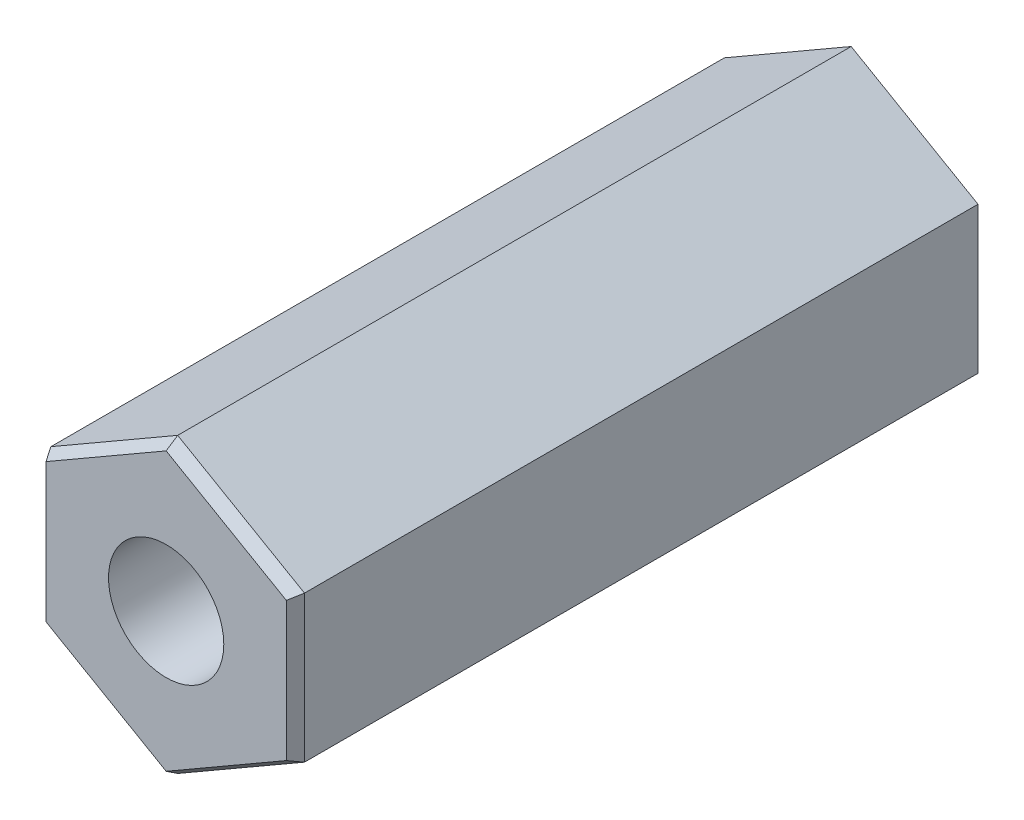
SolidWorks part; units mm, degrees
material "KS26"
ref_plane "正面" through (0, 0, 0) normal (0, 0, 1) x (1, 0, 0)
ref_plane "平面" through (0, 0, 0) normal (0, 1, 0) x (1, 0, 0)
ref_plane "右側面" through (0, 0, 0) normal (1, 0, 0) x (0, 0, -1)
sketch "ｽｹｯﾁ1" plane through (0, 0, 0) normal (0, 0, 1) x (1, 0, 0)
  line L1 (-2.75, 1.5877) -> (-2.75, -1.5877)
  line L2 (-2.75, -1.5877) -> (0, -3.1754)
  line L3 (0, -3.1754) -> (2.75, -1.5877)
  line L4 (2.75, -1.5877) -> (2.75, 1.5877)
  line L5 (2.75, 1.5877) -> (0, 3.1754)
  line L6 (0, 3.1754) -> (-2.75, 1.5877)
  circle A0 centre (0, 0) radius 2.75 construction
  dimension "D1" = 5.5
extrude "ﾎﾞｽ - 押し出し1" add sketch "ｽｹｯﾁ1" along normal mid plane 15
hole_wizard "M3 ねじ穴1" positions "ｽｹｯﾁ2" profile "ｽｹｯﾁ3" tap size "M3" standard "JIS" end condition through all
sketch "ｽｹｯﾁ2" plane through (0, 0, 7.5) normal (0, 0, 1) x (1, 0, 0)
  point P0 (0, 0)
cosmetic thread "穴のねじ山1" parameters "D2"=3
sketch "ｽｹｯﾁ3" plane through (0, 0, 7.5) normal (1, 0, 0) x (0, -1, 0)
  line L0 (0, 0) -> (0, 15)
  line L1 (0, 15) -> (1.25, 15)
  line L2 (1.25, 15) -> (1.25, 0)
  line L5 (1.25, 0) -> (0, 0)
  line L11 (0, -6.35) -> (0, 107.95) construction
  dimension "次ｻｰﾌｪｽまでのねじ下穴ﾄﾞﾘﾙ直径" = 2.5
  dimension "次ｻｰﾌｪｽまでのねじ下穴ﾄﾞﾘﾙの深さ" = 15
sketch "ｽｹｯﾁ4" plane through (0, 0, -7.5) normal (0, 0, -1) x (-1, 0, 0)
  circle A0 centre (0, 0) radius 1.5
  dimension "D1" = 3
extrude "ﾎﾞｽ - 押し出し2" [suppressed] add sketch "ｽｹｯﾁ4" along normal blind 6
chamfer "面取り1" [suppressed] distance 0.25 angle 45
chamfer "面取り2" distance 0.25 angle 30 12 edges at (-1.375, 2.3816, 7.5) (1.375, 2.3816, 7.5) (2.75, 0, 7.5) (1.375, -2.3816, 7.5) (-1.375, -2.3816, 7.5) (-2.75, 0, 7.5) (2.75, 0, -7.5) (1.375, -2.3816, -7.5) (-1.375, -2.3816, -7.5) (-2.75, 0, -7.5) (-1.375, 2.3816, -7.5) (1.375, 2.3816, -7.5)
